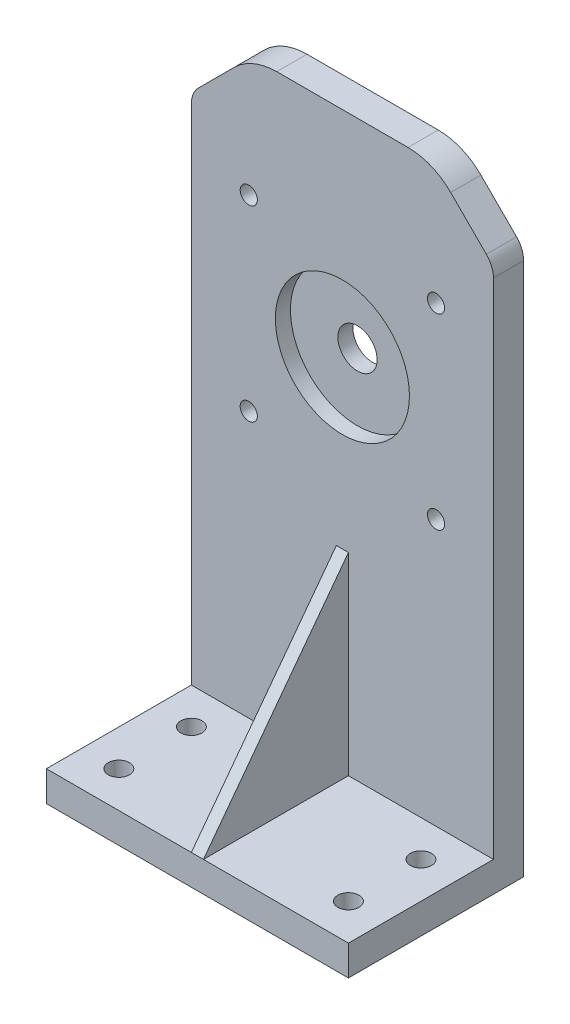
SolidWorks part; units mm, degrees
ref_plane "Front Plane" through (0, 0, 0) normal (0, 0, 1) x (1, 0, 0)
ref_plane "Top Plane" through (0, 0, 0) normal (0, 1, 0) x (1, 0, 0)
ref_plane "Right Plane" through (0, 0, 0) normal (1, 0, 0) x (0, 0, -1)
sketch "Sketch1" plane through (0, 0, 0) normal (0, 1, 0) x (1, 0, 0)
  line L1 (-25, -14.5) -> (25, -14.5)
  line L2 (-25, -14.5) -> (-25, 14.5)
  line L3 (-25, 14.5) -> (25, 14.5)
  line L4 (25, -14.5) -> (25, 14.5)
  line L5 (-25, -14.5) -> (25, 14.5) construction
  line L6 (-25, 14.5) -> (25, -14.5) construction
  point P0 (0, 0)
  dimension "D1" = 50
  dimension "D2" = 29
extrude "Boss-Extrude1" add sketch "Sketch1" along normal blind 5
sketch "Sketch2" plane through (0, 5, 0) normal (0, 1, 0) x (1, 0, 0)
  line L0 (25, -14.5) -> (25, 14.5) construction
  line L1 (-25, 14.5) -> (25, 14.5)
  line L2 (-25, 14.5) -> (-25, 9.5)
  line L3 (-25, 9.5) -> (25, 9.5)
  line L4 (25, 14.5) -> (25, 9.5)
  dimension "D1" = 5
extrude "Boss-Extrude2" add sketch "Sketch2" along normal blind 95
sketch "Sketch3" plane through (0, 0, -9.5) normal (0, 0, 1) x (1, 0, 0)
  line L0 (-25, 5) -> (25, 5) construction
  line L2 (-25, 100) -> (-25, 5) construction
  circle A0 centre (-15.5, 49) radius 1.42
  circle A1 centre (15.5, 49) radius 1.42
  circle A2 centre (15.5, 80) radius 1.42
  circle A3 centre (-15.5, 80) radius 1.42
  dimension "D2" = 2.84
  dimension "D1" = 44
  dimension "D3" = 2
  dimension "D5" = 9.5
  dimension "D4" = 2
extrude "Cut-Extrude1" cut sketch "Sketch3" against normal blind 60
sketch "Sketch4" plane through (0, 0, -9.5) normal (0, 0, 1) x (1, 0, 0)
  circle A0 centre (0, 64.5) radius 11.1
  circle A1 centre (15.5, 49) radius 1.42 construction
  circle A2 centre (15.5, 80) radius 1.42 construction
  dimension "D1" = 22.2
  dimension "D2" = 15.5
  dimension "D3" = 15.5
extrude "Cut-Extrude2" cut sketch "Sketch4" against normal blind 2.5
sketch "Sketch5" plane through (0, 0, -12) normal (0, 0, 1) x (1, 0, 0)
  circle A0 centre (0, 64.5) radius 3.25
  dimension "D1" = 6.5
extrude "Cut-Extrude3" cut sketch "Sketch5" against normal blind 10
sketch "Sketch6" plane through (0, 5, 0) normal (0, 1, 0) x (1, 0, 0)
  line L0 (-25, 9.5) -> (-25, -14.5) construction
  line L1 (25, -14.5) -> (25, 9.5) construction
  line L2 (-25, -14.5) -> (25, -14.5) construction
  line L3 (-25, 9.5) -> (25, 9.5) construction
  circle A0 centre (-19, 3.5) radius 1.75
  circle A1 centre (-19, -8.5) radius 1.75
  circle A2 centre (19, -8.5) radius 1.75
  circle A3 centre (19, 3.5) radius 1.75
  dimension "D1" = 3.5
  dimension "D10" = 3.5
  dimension "D11" = 3.5
  dimension "D12" = 3.5
  dimension "D2" = 6
  dimension "D3" = 6
  dimension "D4" = 6
  dimension "D5" = 6
  dimension "D6" = 6
  dimension "D7" = 6
  dimension "D8" = 6
  dimension "D9" = 6
extrude "Cut-Extrude4" cut sketch "Sketch6" against normal blind 10
sketch "Sketch8" plane through (0, 5, 0) normal (0, 1, 0) x (1, 0, 0)
  line L0 (-25, 9.5) -> (25, 9.5) construction
  line L1 (1, 9.5) -> (-1, 9.5)
  line L2 (1, 9.5) -> (1, -14.5)
  line L3 (1, -14.5) -> (-1, -14.5)
  line L4 (-1, 9.5) -> (-1, -14.5)
  line L5 (-25, -14.5) -> (25, -14.5) construction
  circle A0 centre (-19, 3.5) radius 1.75 construction
  circle A1 centre (19, 3.5) radius 1.75 construction
  dimension "D1" = 20
  dimension "D2" = 20
  dimension "D3" = 0
extrude "Boss-Extrude3" add sketch "Sketch8" along normal blind 32
sketch "Sketch9" plane through (1, 0, 0) normal (1, 0, 0) x (0, 0, -1)
  line L0 (9.5, 37) -> (-14.5, 5)
  line L1 (-14.5, 37) -> (-14.5, 5) construction
  line L2 (-14.5, 5) -> (-14.5, 37)
  line L3 (-14.5, 37) -> (9.5, 37)
extrude "Cut-Extrude5" cut sketch "Sketch9" against normal blind 35
fillet "Fillet1" [suppressed] radius 10
chamfer "Chamfer1" distance 10 angle 45 2 edges at (-25, 100, -12) (25, 100, -12)
fillet "Fillet2" radius 10 2 edges at (15, 100, -12) (-15, 100, -12)
fillet "Fillet3" radius 4 1 edges at (25, 90, -12)
fillet "Fillet4" radius 4 1 edges at (-25, 90, -12)
